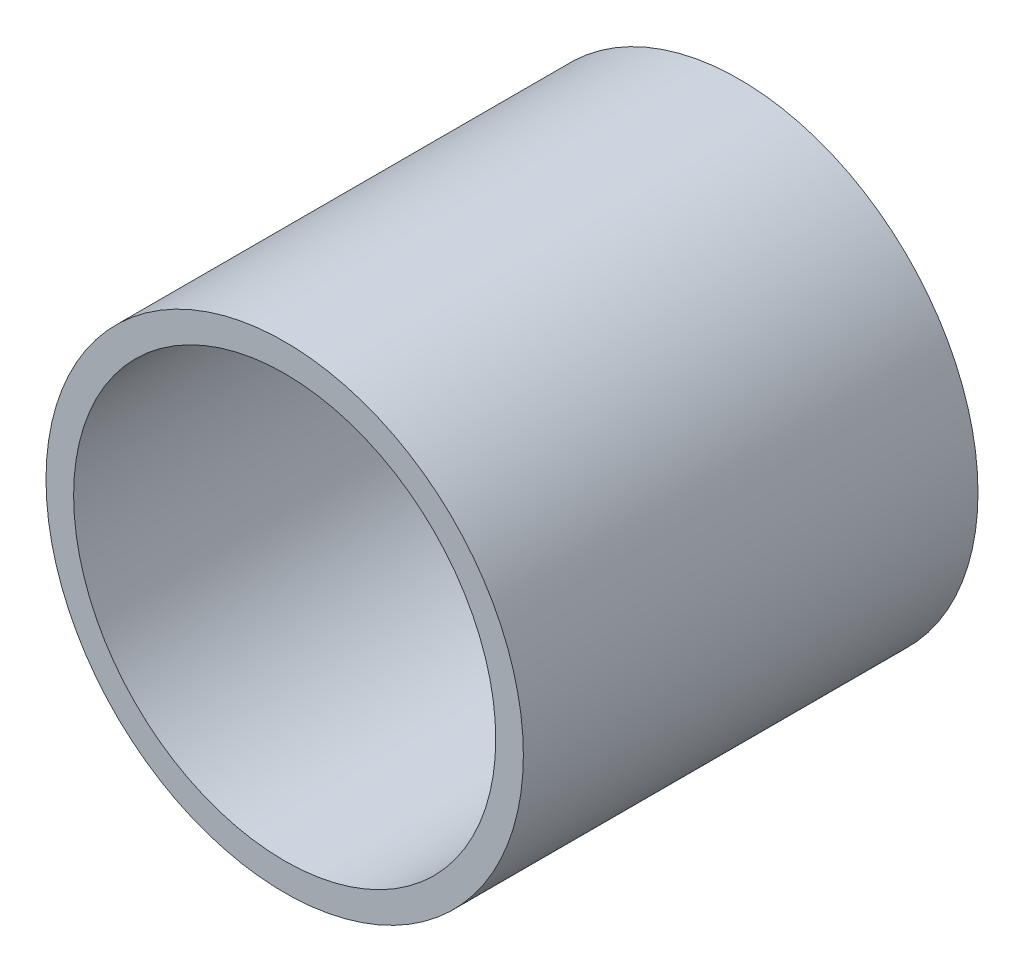
SolidWorks part; units mm, degrees
ref_plane "Front Plane" through (0, 0, 0) normal (0, 0, 1) x (1, 0, 0)
ref_plane "Top Plane" through (0, 0, 0) normal (0, 1, 0) x (1, 0, 0)
ref_plane "Right Plane" through (0, 0, 0) normal (1, 0, 0) x (0, 0, -1)
sketch "Sketch1" plane through (0, 0, 0) normal (0, 0, 1) x (1, 0, 0)
  circle A0 centre (0, 0) radius 2.1
  circle A1 centre (0, 0) radius 1.857
  dimension "D1" = 4.2
extrude "Boss-Extrude1" add sketch "Sketch1" along normal blind 4
